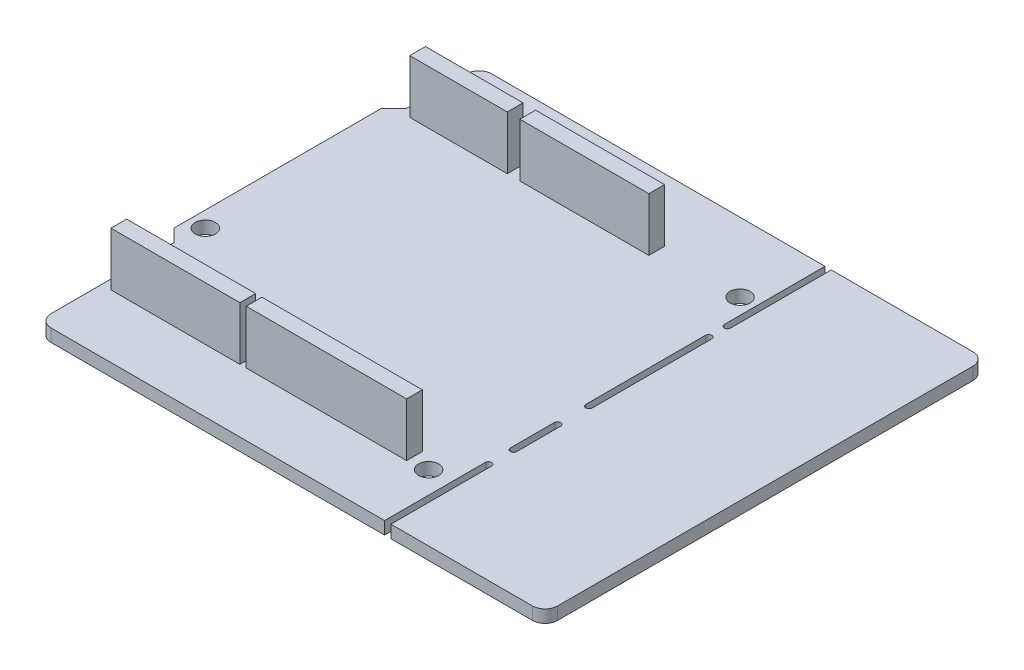
SolidWorks part; units mm, degrees
ref_plane "Płaszczyzna przednia" through (0, 0, 0) normal (0, 0, 1) x (1, 0, 0)
ref_plane "Płaszczyzna górna" through (0, 0, 0) normal (0, 1, 0) x (1, 0, 0)
ref_plane "Płaszczyzna prawa" through (0, 0, 0) normal (1, 0, 0) x (0, 0, -1)
sketch "Szkic2" plane through (0, 0, 0) normal (0, 1, 0) x (1, 0, 0)
  line L0 (-43.3193, -7.1981) -> (-41.3193, -9.1981)
  line L1 (-41.3193, -9.1981) -> (-41.3193, -28.6981)
  line L2 (-39.3193, -30.6981) -> (37.1807, -30.6981)
  line L3 (39.1807, -28.6981) -> (39.1807, 37.3019)
  line L4 (37.1807, 39.3019) -> (-39.3193, 39.3019)
  line L5 (-41.3193, 37.3019) -> (-41.3193, 27.8019)
  line L6 (-41.3193, 27.8019) -> (-43.3193, 25.8019)
  line L7 (-43.3193, 25.8019) -> (-43.3193, -7.1981)
  line L8 (14.1807, 39.3019) -> (14.1807, 23.3019) construction
  line L9 (14.6807, 39.3019) -> (14.6807, 23.3019)
  line L10 (13.6807, 39.3019) -> (13.6807, 23.3019)
  line L11 (14.1807, 20.3019) -> (14.1807, 1.3019) construction
  line L12 (14.6807, 20.3019) -> (14.6807, 1.3019)
  line L13 (13.6807, 20.3019) -> (13.6807, 1.3019)
  line L14 (14.1807, -3.6981) -> (14.1807, -10.6981) construction
  line L15 (14.6807, -3.6981) -> (14.6807, -10.6981)
  line L16 (13.6807, -3.6981) -> (13.6807, -10.6981)
  line L17 (14.1807, -14.6981) -> (14.1807, -30.6981) construction
  line L18 (14.6807, -14.6981) -> (14.6807, -30.6981)
  line L19 (13.6807, -14.6981) -> (13.6807, -30.6981)
  arc A0 (-41.3193, -28.6981) -> (-39.3193, -30.6981) centre (-39.3193, -28.6981) ccw
  arc A1 (37.1807, -30.6981) -> (39.1807, -28.6981) centre (37.1807, -28.6981) ccw
  arc A2 (39.1807, 37.3019) -> (37.1807, 39.3019) centre (37.1807, 37.3019) ccw
  arc A3 (-39.3193, 39.3019) -> (-41.3193, 37.3019) centre (-39.3193, 37.3019) ccw
  arc A4 (14.6807, 39.3019) -> (13.6807, 39.3019) centre (14.1807, 39.3019) ccw
  arc A5 (13.6807, 23.3019) -> (14.6807, 23.3019) centre (14.1807, 23.3019) ccw
  arc A6 (14.6807, 20.3019) -> (13.6807, 20.3019) centre (14.1807, 20.3019) ccw
  arc A7 (13.6807, 1.3019) -> (14.6807, 1.3019) centre (14.1807, 1.3019) ccw
  arc A8 (14.6807, -3.6981) -> (13.6807, -3.6981) centre (14.1807, -3.6981) ccw
  arc A9 (13.6807, -10.6981) -> (14.6807, -10.6981) centre (14.1807, -10.6981) ccw
  arc A10 (14.6807, -14.6981) -> (13.6807, -14.6981) centre (14.1807, -14.6981) ccw
  arc A11 (13.6807, -30.6981) -> (14.6807, -30.6981) centre (14.1807, -30.6981) ccw
  circle A12 centre (10.1807, -20.1981) radius 1.6
  circle A13 centre (11.1807, 28.3019) radius 1.6
  circle A14 centre (-40.8193, -4.6981) radius 1.6
  point P2 (14.1807, 31.3019)
  point P25 (14.1807, 10.8019)
  point P32 (14.1807, -7.1981)
  point P37 (14.1807, -22.6981)
  point P50 (-40.7667, -4.5567)
  dimension "D4" = 2
  dimension "D8" = 1
  dimension "D16" = 3.2
  dimension "D1" = 80.5
  dimension "D2" = 70
  dimension "D3" = 82.5
  dimension "D5" = 11.5
  dimension "D6" = 135
  dimension "D7" = 21.5
  dimension "D9" = 24.5
  dimension "D10" = 16
  dimension "D11" = 19
  dimension "D12" = 3
  dimension "D13" = 5
  dimension "D14" = 7
  dimension "D15" = 4
  dimension "D17" = 2.5
  dimension "D18" = 26
  dimension "D19" = 10.5
  dimension "D20" = 53.5
  dimension "D21" = 54.5
  dimension "D22" = 11
extrude "Dodanie-wyciągnięcie1" add sketch "Szkic2" along normal blind 2 contours A10 L18 L2 A1 L3 A2 L4 L9 A5 L10 A3 L5 L6 L7 L0 L1 A0 L19 A14 A13 A12 A9 L16 A8 L15 A7 L13 A6 L12
sketch "Szkic3" plane through (0, 2, 0) normal (0, 1, 0) x (1, 0, 0)
  line L0 (-41.3193, -9.1981) -> (-41.3193, -28.6981) construction
  line L1 (-39.8193, 26.8019) -> (-24.3193, 26.8019)
  line L2 (-39.8193, 26.8019) -> (-39.8193, 29.3019)
  line L3 (-39.8193, 29.3019) -> (-24.3193, 29.3019)
  line L4 (-24.3193, 26.8019) -> (-24.3193, 29.3019)
  line L5 (-22.3193, 26.8019) -> (-1.8193, 26.8019)
  line L6 (-22.3193, 26.8019) -> (-22.3193, 29.3019)
  line L7 (-22.3193, 29.3019) -> (-1.8193, 29.3019)
  line L8 (-1.8193, 26.8019) -> (-1.8193, 29.3019)
  line L9 (-39.8193, -20.6981) -> (-19.3193, -20.6981)
  line L10 (-39.8193, -20.6981) -> (-39.8193, -18.1981)
  line L11 (-39.8193, -18.1981) -> (-19.3193, -18.1981)
  line L12 (-19.3193, -20.6981) -> (-19.3193, -18.1981)
  line L13 (-18.3193, -20.6981) -> (7.1807, -20.6981)
  line L14 (-18.3193, -20.6981) -> (-18.3193, -18.1981)
  line L15 (-18.3193, -18.1981) -> (7.1807, -18.1981)
  line L16 (7.1807, -20.6981) -> (7.1807, -18.1981)
  line L18 (13.6807, 39.3019) -> (-39.3193, 39.3019) construction
  line L19 (-39.3193, -30.6981) -> (13.6807, -30.6981) construction
  dimension "D1" = 2.5
  dimension "D2" = 15.5
  dimension "D3" = 2.5
  dimension "D4" = 20.5
  dimension "D5" = 2.5
  dimension "D6" = 20.5
  dimension "D7" = 2.5
  dimension "D8" = 25.5
  dimension "D9" = 1.5
  dimension "D10" = 1
  dimension "D11" = 2
  dimension "D12" = 10
  dimension "D13" = 10
extrude "Dodanie-wyciągnięcie2" add sketch "Szkic3" along normal blind 8.5
